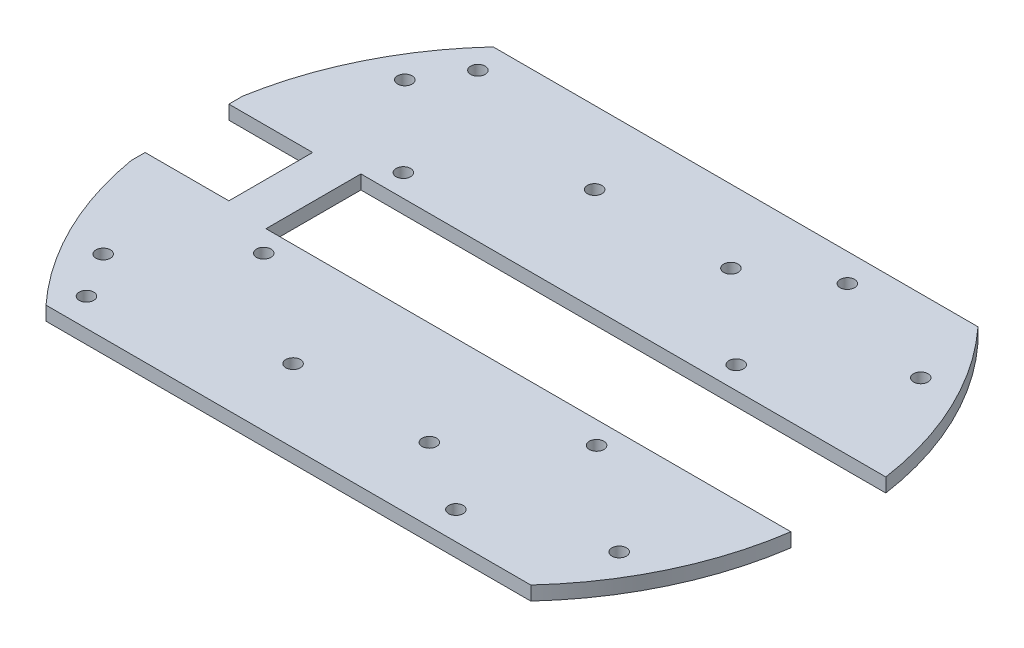
SolidWorks part; units mm, degrees
ref_plane "Front Plane" through (0, 0, 0) normal (0, 0, 1) x (1, 0, 0)
ref_plane "Top Plane" through (0, 0, 0) normal (0, 1, 0) x (1, 0, 0)
ref_plane "Right Plane" through (0, 0, 0) normal (1, 0, 0) x (0, 0, -1)
sketch "Sketch1" plane through (0, 0, 0) normal (0, 1, 0) x (1, 0, 0)
  line L0 (-73.9169, 12.7) -> (-73.9169, -12.7)
  line L1 (-55.1228, -50.8575) -> (55.1228, -50.8575)
  line L2 (-55.1228, 50.8575) -> (55.1228, 50.8575)
  line L3 (-55.1228, -50.8575) -> (38.1, -50.8575) construction
  line L4 (-73.9169, 0) -> (-45.1587, 0) construction
  line L5 (74.2191, 10.795) -> (-45.1587, 10.795)
  line L6 (0, 50.8575) -> (0, -50.8575) construction
  line L7 (74.2191, -10.795) -> (-45.1587, -10.795)
  line L8 (-45.1587, 10.795) -> (-45.1587, -10.795)
  line L9 (41.5823, -13.335) -> (41.5823, 13.335) construction
  line L10 (35.1053, 15.875) -> (35.1053, 10.795) construction
  line L11 (35.1053, 15.875) -> (-40.5944, 15.875) construction
  line L12 (-40.5944, 15.875) -> (-40.5944, -15.875) construction
  line L13 (-40.5944, -15.875) -> (35.1053, -15.875) construction
  line L14 (35.1053, -15.875) -> (35.1053, 15.875) construction
  line L15 (-45.1587, 0) -> (-40.5944, 0) construction
  line L16 (41.4553, 19.05) -> (-51.5087, 19.05) construction
  line L17 (41.4553, 10.795) -> (41.4553, 19.05) construction
  line L18 (-51.5087, 19.05) -> (-51.5087, -19.05) construction
  arc A0 (-73.9169, -12.7) -> (-55.1228, -50.8575) centre (0, 0) ccw
  arc A1 (-55.1228, 50.8575) -> (-73.9169, 12.7) centre (0, 0) ccw
  arc A2 (55.1228, -50.8575) -> (74.2191, -10.795) centre (0, 0) ccw
  circle A3 centre (31.75, 44.5075) radius 1.651
  arc A4 (74.2191, 10.795) -> (55.1228, 50.8575) centre (0, 0) ccw
  circle A5 centre (35.1053, 15.875) radius 1.651
  circle A6 centre (35.1053, -15.875) radius 1.651
  circle A7 centre (-40.5944, -15.875) radius 1.651
  circle A8 centre (-40.5944, 15.875) radius 1.651
  circle A9 centre (31.75, -44.5075) radius 1.651
  circle A10 centre (31.75, -44.5075) radius 1.651 construction
  circle A11 centre (-52.2677, -44.5075) radius 1.651
  circle A12 centre (-52.2677, 44.5075) radius 1.651
  circle A13 centre (-52.2677, -44.5075) radius 1.651 construction
  circle A14 centre (-58.6769, 34.29) radius 1.651
  circle A15 centre (-15.4969, 34.29) radius 1.651
  circle A16 centre (-15.4969, -34.29) radius 1.651
  circle A17 centre (-58.6769, -34.29) radius 1.651
  circle A18 centre (15.4969, -34.29) radius 1.651
  circle A19 centre (58.6769, -34.29) radius 1.651
  circle A20 centre (58.6769, 34.29) radius 1.651
  circle A21 centre (15.4969, 34.29) radius 1.651
  dimension "D1" = 150
  dimension "D2" = 25.4
  dimension "D3" = 21.59
  dimension "D4" = 86.741
  dimension "D5" = 3.175
  dimension "D6" = 6.35
  dimension "D7" = 10.9143
extrude "Boss-Extrude1" add sketch "Sketch1" along normal blind 3.175
sketch "Sketch2" plane through (0, 3.175, 0) normal (0, 1, 0) x (1, 0, 0)
  line L0 (-73.9169, 9.525) -> (-54.8669, 9.525)
  line L1 (-73.9169, 12.7) -> (-73.9169, -12.7) construction
  line L2 (-54.8669, 9.525) -> (-54.8669, -9.525)
  line L3 (-54.8669, -9.525) -> (-73.9169, -9.525)
  line L4 (-73.9169, 0) -> (-54.8669, 0) construction
  line L5 (-73.9169, 9.525) -> (-73.9169, -9.525)
  dimension "D1" = 19.05
  dimension "D2" = 19.05
extrude "Cut-Extrude1" cut sketch "Sketch2" against normal up to surface (3.175 mm away) up to face at (58.6769, 0, -35.941)
